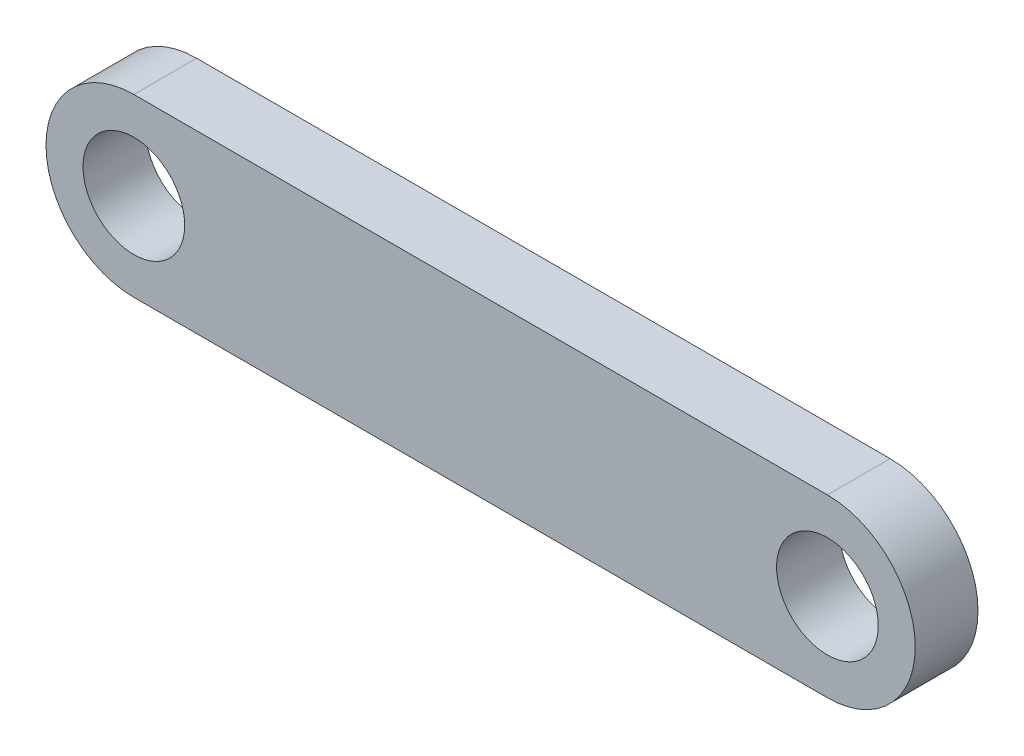
SolidWorks part; units mm, degrees
material "Hexcel AS4C (3000 丝)"
ref_plane "前视基准面" through (0, 0, 0) normal (0, 0, 1) x (1, 0, 0)
ref_plane "上视基准面" through (0, 0, 0) normal (0, 1, 0) x (1, 0, 0)
ref_plane "右视基准面" through (0, 0, 0) normal (1, 0, 0) x (0, 0, -1)
sketch "草图1" plane through (0, 0, 0) normal (0, 0, 1) x (1, 0, 0)
  line L0 (-750.8457, 0) -> (36791.4387, 0) construction
  line L1 (0, -7) -> (55.26, -7)
  line L2 (0, 7) -> (55.26, 7)
  circle A0 centre (0, 0) radius 4.05
  circle A1 centre (55.26, 0) radius 4.05
  circle A2 centre (0, 0) radius 7
  circle A3 centre (55.26, 0) radius 7
  dimension "D1" = 8.1
  dimension "D2" = 55.26
  dimension "D3" = 14
extrude "凸台-拉伸1" add sketch "草图1" along normal blind 5 contours A2 L0 A3 L2 | A3 L0 A1 | L0 A2 L1 A3 | L0 A3 A1 | A2 L0 A0 | L0 A2 A0
